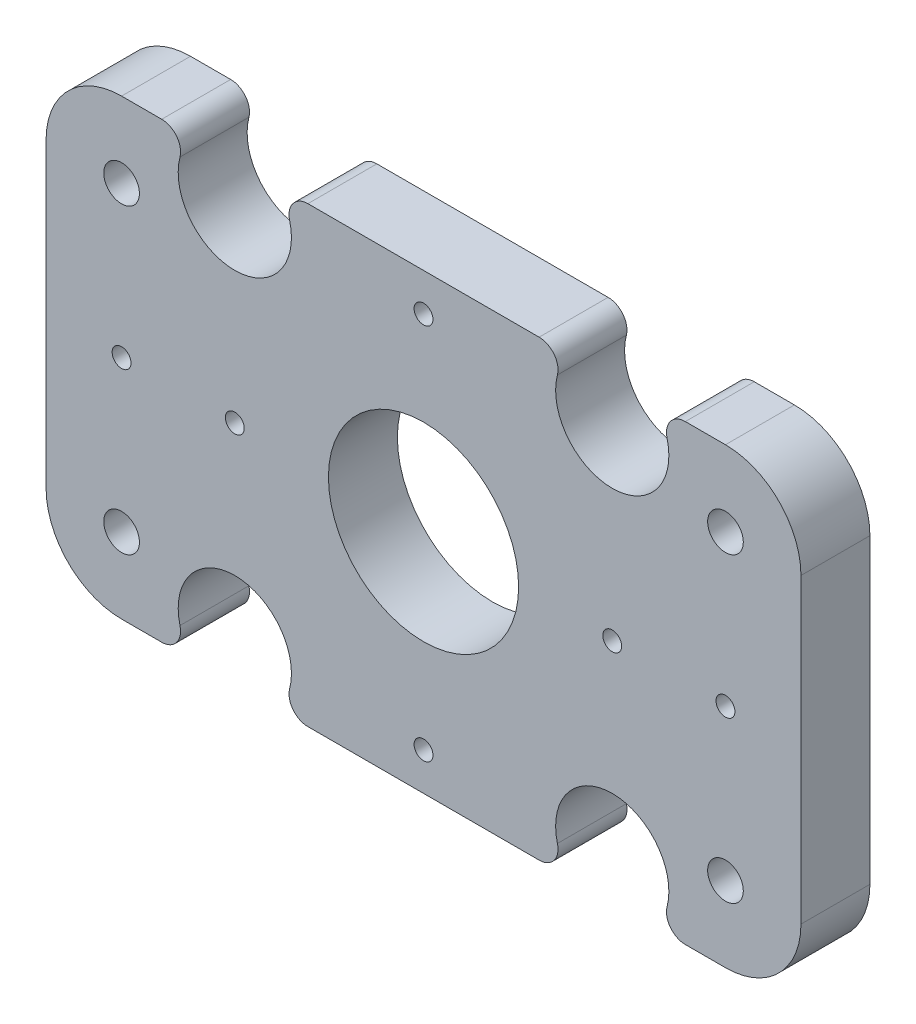
SolidWorks part; units mm, degrees
material "Balsa"
ref_plane "Front Plane" through (0, 0, 0) normal (0, 0, 1) x (1, 0, 0)
ref_plane "Top Plane" through (0, 0, 0) normal (0, 1, 0) x (1, 0, 0)
ref_plane "Right Plane" through (0, 0, 0) normal (1, 0, 0) x (0, 0, -1)
sketch "Sketch1" plane through (0, 0, 0) normal (0, 0, 1) x (1, 0, 0)
  line L1 (0, 0) -> (-38.1, 0)
  line L2 (0, 0) -> (0, 38.1)
  line L3 (0, 38.1) -> (-38.1, 38.1)
  line L4 (-38.1, 0) -> (-38.1, 38.1)
  dimension "D1" = 38.1
extrude "Boss-Extrude1" add sketch "Sketch1" along normal blind 5.8
sketch "Sketch2" plane through (0, 0, 5.8) normal (0, 0, 1) x (1, 0, 0)
  line L0 (-19.05, 19.05) -> (-38.1, 19.05) construction
  line L1 (-38.1, 38.1) -> (-38.1, 0) construction
  line L2 (-19.05, 19.05) -> (-19.05, 0) construction
  line L3 (-38.1, 0) -> (0, 0) construction
  circle A0 centre (-19.05, 19.05) radius 8
  dimension "D1" = 16
extrude "Cut-Extrude1" cut sketch "Sketch2" against normal blind 12.7
sketch "Sketch4" plane through (0, 0, 5.8) normal (0, 0, 1) x (1, 0, 0)
  line L0 (-19.05, 38.1) -> (-19.05, 0) construction
  line L1 (0, 38.1) -> (-38.1, 38.1) construction
  line L2 (-38.1, 0) -> (0, 0) construction
  line L3 (-19.05, 19.05) -> (-38.1, 19.05) construction
  line L4 (-38.1, 38.1) -> (-38.1, 0) construction
  circle A0 centre (-34.925, 19.05) radius 0.7937
  circle A1 centre (-19.05, 34.925) radius 0.7937
  circle A2 centre (-3.175, 19.05) radius 0.7938
  circle A3 centre (-19.05, 3.175) radius 0.7937
  dimension "D2" = 1.5875
  dimension "D1" = 3.175
  dimension "D3" = 4
extrude "Cut-Extrude3" cut sketch "Sketch4" against normal through all
sketch "Sketch6" plane through (0, 0, 5.8) normal (0, 0, 1) x (1, 0, 0)
  line L0 (0, 38.1) -> (-38.1, 38.1) construction
  line L1 (0, 0) -> (12.7, 0)
  line L2 (0, 0) -> (0, 38.1)
  line L3 (0, 38.1) -> (12.7, 38.1)
  line L4 (12.7, 0) -> (12.7, 38.1)
  line L5 (-19.05, 0) -> (-19.05, 38.1) construction
  line L6 (-38.1, 0) -> (0, 0) construction
  line L7 (-50.8, 0) -> (-50.8, 38.1)
  line L8 (-38.1, 38.1) -> (-50.8, 38.1)
  line L9 (-38.1, 0) -> (-38.1, 38.1)
  line L10 (-38.1, 0) -> (-50.8, 0)
  dimension "D1" = 12.7
extrude "Boss-Extrude2" add sketch "Sketch6" against normal through all
sketch "Sketch3" plane through (0, 0, 5.8) normal (0, 0, 1) x (1, 0, 0)
  line L0 (-38.1, 38.1) -> (0, 0) construction
  line L1 (0, 38.1) -> (-38.1, 0) construction
  line L2 (-19.05, 0) -> (-19.05, 38.1) construction
  line L3 (-50.8, 0) -> (12.7, 0) construction
  line L4 (-38.1, 19.05) -> (0, 19.05) construction
  line L5 (0, 38.1) -> (0, 0) construction
  line L6 (12.7, 38.1) -> (-50.8, 38.1) construction
  line L7 (12.7, 38.1) -> (-50.8, 38.1) construction
  line L8 (-38.1, 38.1) -> (-38.1, 0) construction
  line L9 (-38.1, 38.1) -> (-31.3752, 38.1)
  line L10 (0, 38.1) -> (-6.7248, 38.1)
  line L11 (-38.1, 38.1) -> (-38.4748, 38.1)
  line L12 (0, 38.1) -> (0.3748, 38.1)
  line L13 (0, 0) -> (-6.7248, 0)
  line L14 (-38.1, 0) -> (-31.3752, 0)
  line L15 (-38.1, 0) -> (-38.4748, 0)
  line L16 (0, 0) -> (0.3748, 0)
  arc A0 (-38.4748, 38.1) -> (-31.3752, 38.1) centre (-34.925, 34.925) ccw
  arc A1 (0.3748, 38.1) -> (-6.7248, 38.1) centre (-3.175, 34.925) cw
  arc A2 (0.3748, 0) -> (-6.7248, 0) centre (-3.175, 3.175) ccw
  arc A3 (-38.4748, 0) -> (-31.3752, 0) centre (-34.925, 3.175) cw
  dimension "D2" = 31.75
  dimension "D1" = 4.7625
extrude "Cut-Extrude2" cut sketch "Sketch3" against normal through all
hole_wizard "M3x0.5 Tapped Hole1" positions "Sketch8" profile "Sketch7" tap size "M3x0.5" standard "Ansi Metric"
sketch "Sketch8" plane through (0, 0, 5.8) normal (0, 0, 1) x (1, 0, 0)
  line L0 (-44.45, 38.1) -> (-44.45, 0) construction
  line L1 (-38.4748, 38.1) -> (-50.8, 38.1) construction
  line L2 (-50.8, 0) -> (-38.4748, 0) construction
  line L4 (-50.8, 31.75) -> (12.7, 31.75) construction
  line L5 (-50.8, 38.1) -> (-50.8, 0) construction
  line L6 (12.7, 0) -> (12.7, 38.1) construction
  line L7 (-50.8, 19.05) -> (12.7, 19.05) construction
  line L9 (-19.05, 38.1) -> (-19.05, 0) construction
  line L10 (-6.7248, 38.1) -> (-31.3752, 38.1) construction
  line L11 (-31.3752, 0) -> (-6.7248, 0) construction
  point P0 (-44.45, 31.75)
  point P39 (6.35, 31.75)
  point P41 (6.35, 6.35)
  point P42 (-44.45, 6.35)
  dimension "D1" = 6.35
  dimension "D2" = 6.35
sketch "Sketch7" plane through (-44.45, 31.75, 5.8) normal (1, 0, 0) x (0, -1, 0)
  line L0 (0, 0) -> (0, 8.2511)
  line L1 (0, 8.2511) -> (1.25, 7.5)
  line L2 (1.25, 7.5) -> (1.25, 6)
  line L3 (1.25, 6) -> (1.5, 6)
  line L4 (1.5, 6) -> (1.5, 0)
  line L5 (1.5, 0) -> (0, 0)
  line L10 (0, 8.2511) -> (-1.25, 7.5) construction
  line L11 (0, -6.35) -> (0, 107.95) construction
  dimension "Tap Drill Dia." = 2.5
  dimension "Tap Drill Depth" = 7.5
  dimension "Thread Major Dia." = 3
  dimension "Thread Depth" = 6
  dimension "Drill Angle" = 118
sketch "Sketch9" plane through (0, 0, 5.8) normal (0, 0, 1) x (1, 0, 0)
  line L0 (-44.45, 31.75) -> (-44.45, 6.35) construction
  line L1 (6.35, 31.75) -> (6.35, 6.35) construction
  circle A0 centre (-44.45, 19.05) radius 0.7937
  circle A1 centre (6.35, 19.05) radius 0.7938
  dimension "D1" = 1.5875
extrude "Cut-Extrude4" cut sketch "Sketch9" against normal through all
fillet "Fillet1" radius 6.35 4 edges at (12.7, 38.1, 2.9) (12.7, 0, 2.9) (-50.8, 0, 2.9) (-50.8, 38.1, 2.9)
fillet "Fillet2" radius 1.5875 6 edges at (0.3748, 38.1, 2.9) (-6.7248, 38.1, 2.9) (-31.3752, 38.1, 2.9) (-6.7248, 0, 2.9) (-38.4748, 0, 2.9) (-31.3752, 0, 2.9)
